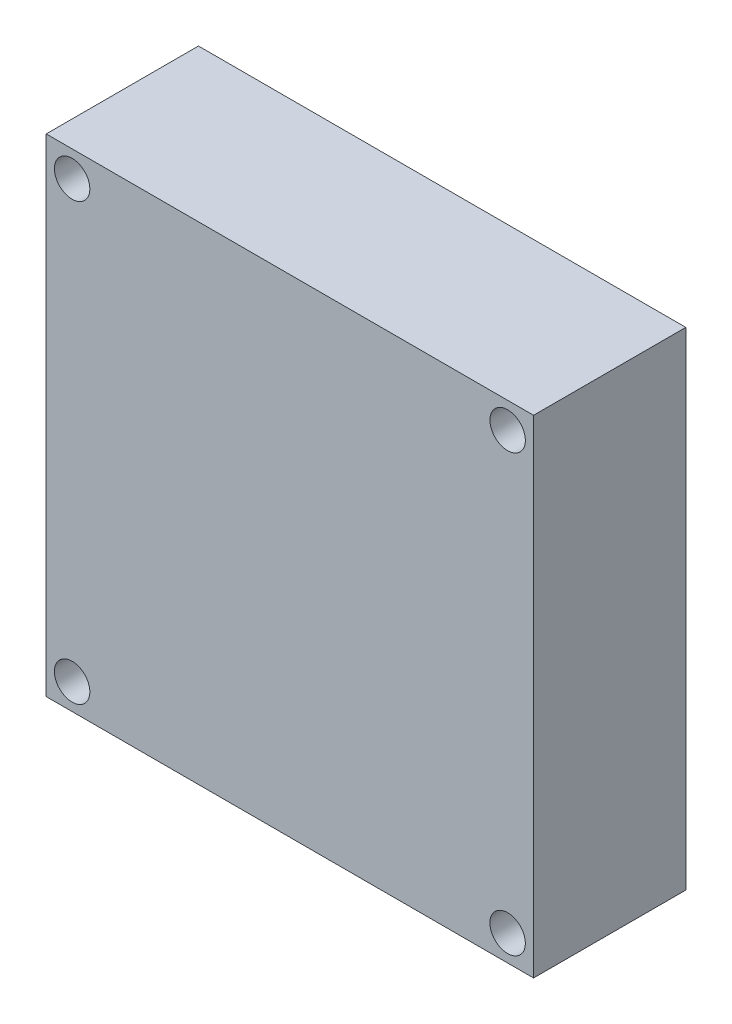
SolidWorks part; units mm, degrees
ref_plane "Front Plane" through (0, 0, 0) normal (0, 0, 1) x (1, 0, 0)
ref_plane "Top Plane" through (0, 0, 0) normal (0, 1, 0) x (1, 0, 0)
ref_plane "Right Plane" through (0, 0, 0) normal (1, 0, 0) x (0, 0, -1)
sketch "Sketch1" plane through (0, 0, 0) normal (0, 0, 1) x (1, 0, 0)
  line L1 (-40.005, -40.005) -> (40.005, -40.005)
  line L2 (-40.005, -40.005) -> (-40.005, 40.005)
  line L3 (-40.005, 40.005) -> (40.005, 40.005)
  line L4 (40.005, -40.005) -> (40.005, 40.005)
  line L5 (-40.005, -40.005) -> (40.005, 40.005) construction
  line L6 (-40.005, 40.005) -> (40.005, -40.005) construction
  point P0 (0, 0)
  dimension "D1" = 80.01
  dimension "D2" = 80.01
extrude "Boss-Extrude1" add sketch "Sketch1" along normal blind 24.9936
sketch "Sketch2" plane through (0, 0, 24.9936) normal (0, 0, 1) x (1, 0, 0)
  line L2 (-40.005, 40.005) -> (-40.005, -40.005) construction
  line L3 (40.005, 40.005) -> (-40.005, 40.005) construction
  line L4 (0, 0) -> (11.4694, 0)
  circle A0 centre (-35.7505, 35.7505) radius 2.9083
  circle A1 centre (35.7505, 35.7505) radius 2.9083
  circle A2 centre (35.7505, -35.7505) radius 2.9083
  circle A3 centre (-35.7505, -35.7505) radius 2.9083
  dimension "D1" = 5.8166
  dimension "D2" = 71.501
  dimension "D3" = 5.8166
  dimension "D4" = 4.2545
  dimension "D5" = 4.2545
  dimension "D6" = 0
extrude "Cut-Extrude1" cut sketch "Sketch2" against normal through all contours A0 | A1 | A3 | A2
